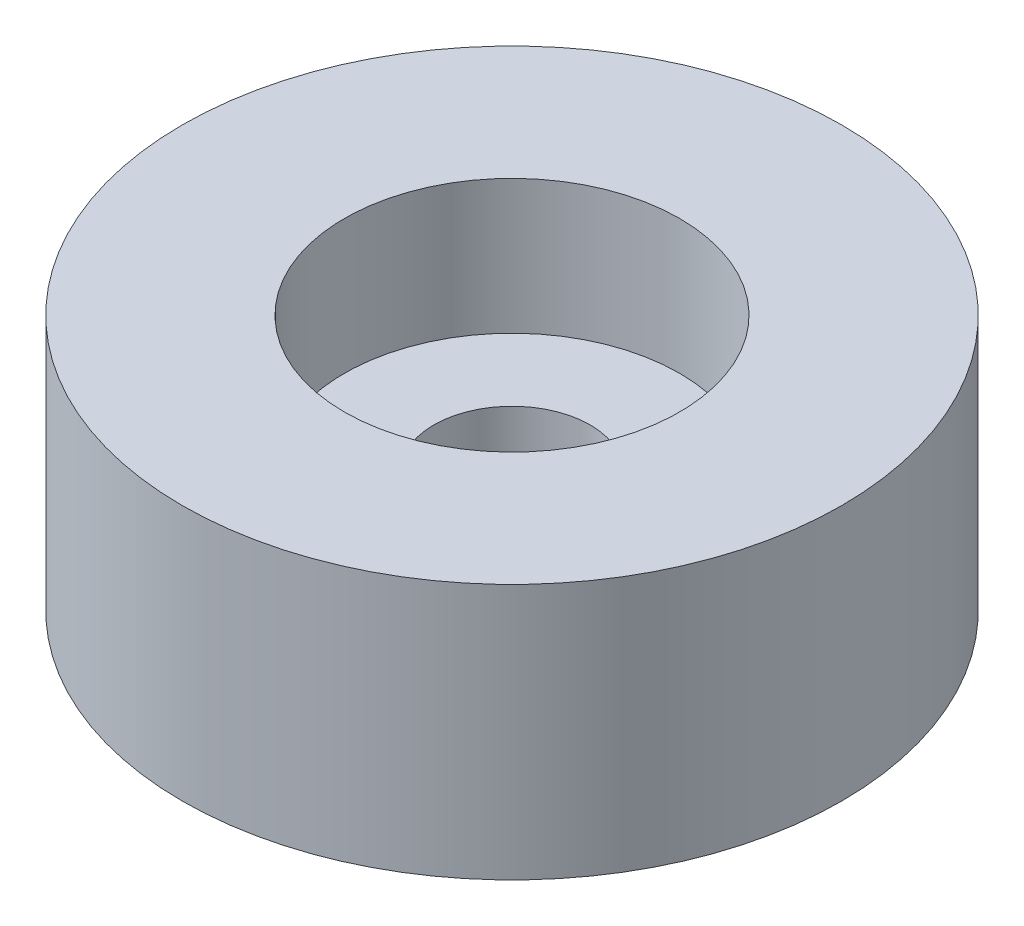
SolidWorks part; units mm, degrees
ref_plane "Front Plane" through (0, 0, 0) normal (0, 0, 1) x (1, 0, 0)
ref_plane "Top Plane" through (0, 0, 0) normal (0, 1, 0) x (1, 0, 0)
ref_plane "Right Plane" through (0, 0, 0) normal (1, 0, 0) x (0, 0, -1)
sketch "Sketch1" plane through (0, 0, 0) normal (0, 1, 0) x (1, 0, 0)
  circle A0 centre (0, 0) radius 29.5
extrude "Boss-Extrude1" add sketch "Sketch1" along normal blind 22.9
sketch "Sketch2" plane through (0, 0, 0) normal (0, -1, 0) x (1, 0, 0)
  line L1 (12.2459, 12.2459) -> (0, 17.3183)
  line L2 (0, 17.3183) -> (-12.2459, 12.2459)
  line L3 (-12.2459, 12.2459) -> (-17.3183, 0)
  line L4 (-17.3183, 0) -> (-12.2459, -12.2459)
  line L5 (-12.2459, -12.2459) -> (0, -17.3183)
  line L6 (0, -17.3183) -> (12.2459, -12.2459)
  line L7 (12.2459, -12.2459) -> (17.3183, 0)
  line L8 (17.3183, 0) -> (12.2459, 12.2459)
  circle A0 centre (0, 0) radius 16 construction
extrude "Cut-Extrude1" cut sketch "Sketch2" against normal blind 3
sketch "Sketch3" plane through (0, 3, 0) normal (0, -1, 0) x (1, 0, 0)
  circle A0 centre (0, 0) radius 7
extrude "Cut-Extrude2" cut sketch "Sketch3" against normal blind 8
sketch "Sketch4" plane through (0, 22.9, 0) normal (0, 1, 0) x (1, 0, 0)
  circle A0 centre (0, 0) radius 15
extrude "Cut-Extrude3" cut sketch "Sketch4" against normal blind 12
